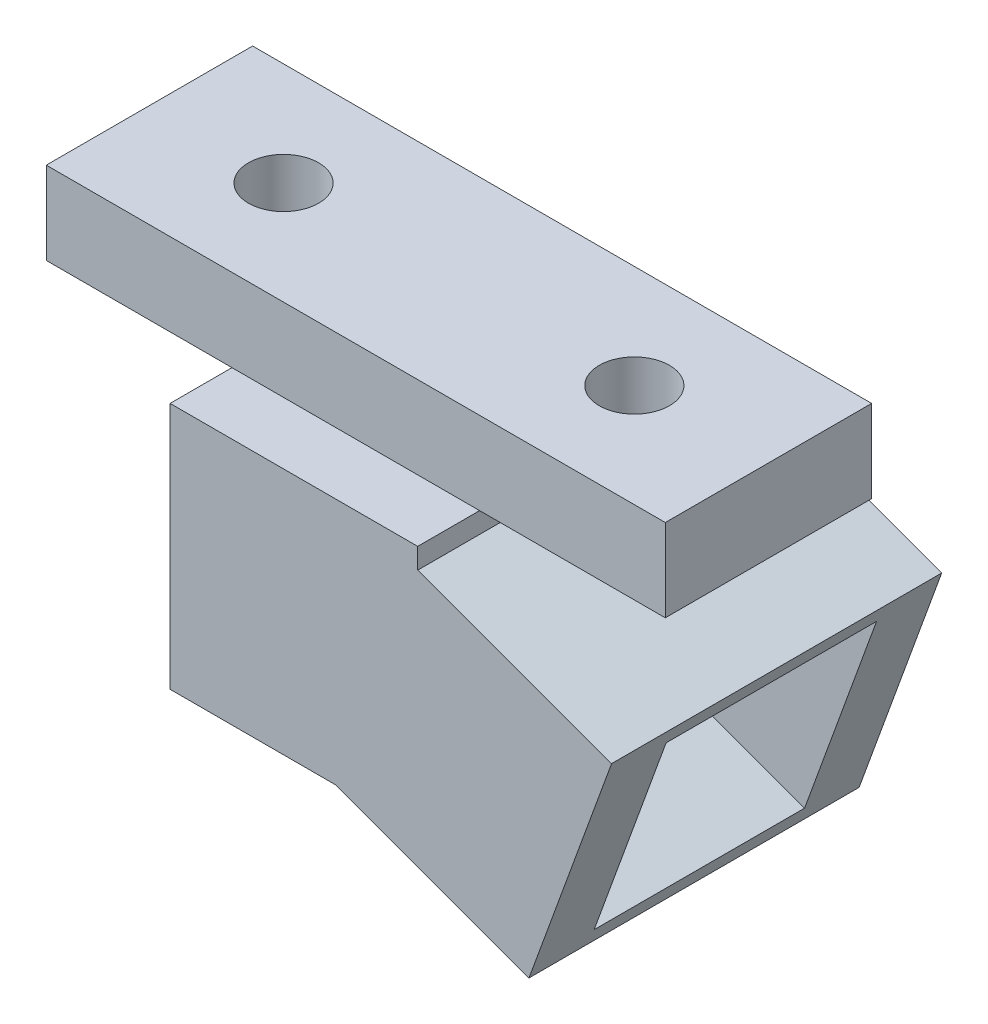
SolidWorks part; units mm, degrees
ref_plane "前视基准面" through (0, 0, 0) normal (0, 0, 1) x (1, 0, 0)
ref_plane "上视基准面" through (0, 0, 0) normal (0, 1, 0) x (1, 0, 0)
ref_plane "右视基准面" through (0, 0, 0) normal (1, 0, 0) x (0, 0, -1)
other "Configuration Table"
sketch "草图1" plane through (0, 0, 0) normal (0, 1, 0) x (1, 0, 0)
  line L0 (7.5, 5) -> (7.5, 0) construction
  line L1 (0, 0) -> (15, 0)
  line L2 (0, 0) -> (0, 5)
  line L3 (0, 5) -> (15, 5)
  line L4 (15, 0) -> (15, 5)
  circle A0 centre (3.25, 2.5) radius 0.85
  circle A1 centre (11.75, 2.5) radius 0.85
  point P12 (0, 2.5)
  dimension "D3" = 1.7
  dimension "D1" = 15
  dimension "D2" = 5
  dimension "D4" = 8.5
extrude "凸台-拉伸1" add sketch "草图1" along normal blind 2 contours L2 L1 L4 L3 | A0 | A1
sketch "草图2" plane through (0, 0, 0) normal (0, -1, 0) x (1, 0, 0)
  line L7 (0, 0) -> (15, 0) construction
  line L9 (0, -5) -> (15, -5) construction
  line L11 (7.5, 0) -> (7.5, -5) construction
  line L13 (10.5, 1.5) -> (4.5, 1.5)
  line L14 (4.5, 1.5) -> (4.5, -6.5)
  line L16 (10.5, 1.5) -> (10.5, -6.5)
  line L17 (0, -2.5) -> (15, -2.5) construction
  line L18 (0, 0) -> (0, -5) construction
  line L19 (15, 0) -> (15, -5) construction
  line L20 (10.5, -6.5) -> (4.5, -6.5)
  point P11 (7.5, 1.5)
  point P12 (7.5, -6.9299)
  dimension "D1" = 6
  dimension "D2" = 8
extrude "凸台-拉伸3" add sketch "草图2" along normal blind 6
sketch "草图6" plane through (0, 0, -6.5) normal (0, 0, -1) x (-1, 0, 0)
  line L0 (-10.5, -0.5) -> (-10.5, -6)
  line L1 (-10.5, -6) -> (-10.5, 0) construction
  line L2 (-10.5, -6) -> (-8.4982, -6)
  line L3 (-4.5, -6) -> (-10.5, -6) construction
  line L4 (-8.4982, -6) -> (-10.5, -0.5)
  dimension "D1" = 20
  dimension "D2" = 5.5
extrude "切除-拉伸2" cut sketch "草图6" against normal up to surface (8 mm away) up to face at (7.5, -3, 1.5)
sketch "草图7" plane through (9.4324, -3.4331, 0) normal (0.9397, -0.342, 0) x (0, 0, -1)
  line L0 (-1.5, 0.1949) -> (6.5, 0.1949) construction
  line L1 (-1.5, 3.1214) -> (-1.5, -2.7316) construction
  line L2 (6.5, -2.7316) -> (6.5, 3.1214) construction
  line L3 (5.05, 2.7449) -> (-0.05, 2.7449)
  line L4 (-1.5, 3.1214) -> (6.5, 3.1214) construction
  line L5 (2.5, 3.1214) -> (2.5, -2.7316) construction
  line L6 (-1.5, -2.7316) -> (6.5, -2.7316) construction
  line L7 (-0.05, 2.7449) -> (-0.05, -2.3551)
  line L8 (5.05, -2.3551) -> (-0.05, -2.3551)
  line L9 (5.05, 2.7449) -> (5.05, -2.3551)
  point P16 (-0.05, 0.1949)
  point P18 (2.5, -2.3551)
  point P19 (2.5, 2.7449)
  dimension "D1" = 5.1
  dimension "D2" = 5.1
extrude "切除-拉伸3" cut sketch "草图7" against normal blind 2
sketch "草图10" plane through (9.4324, -3.4331, 0) normal (0.9397, -0.342, 0) x (0, 0, -1)
  line L1 (-0.05, 2.7449) -> (5.05, 2.7449)
  line L2 (-0.05, 2.7449) -> (-0.05, -2.3551)
  line L3 (-0.05, -2.3551) -> (5.05, -2.3551)
  line L4 (5.05, 2.7449) -> (5.05, -2.3551)
  line L5 (-1.5, 3.1214) -> (6.5, 3.1214)
  line L6 (-1.5, 3.1214) -> (-1.5, -2.7316)
  line L7 (-1.5, -2.7316) -> (6.5, -2.7316)
  line L8 (6.5, 3.1214) -> (6.5, -2.7316)
extrude "凸台-拉伸4" add sketch "草图10" along normal blind 5
